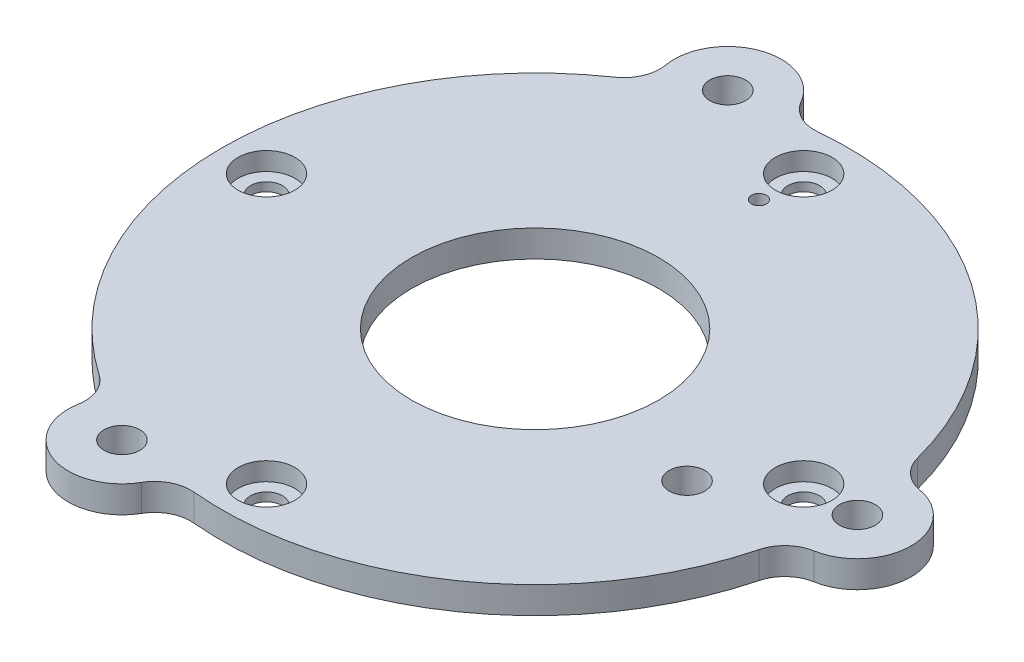
SolidWorks part; units mm, degrees
material "1060 Alloy"
ref_plane "Front Plane" through (0, 0, 0) normal (0, 0, 1) x (1, 0, 0)
ref_plane "Top Plane" through (0, 0, 0) normal (0, 1, 0) x (1, 0, 0)
ref_plane "Right Plane" through (0, 0, 0) normal (1, 0, 0) x (0, 0, -1)
sketch "Sketch1" plane through (0, 0, 0) normal (0, 1, 0) x (1, 0, 0)
  circle A0 centre (0, 0) radius 17.5
  dimension "D1" = 35
extrude "Boss-Extrude1" add sketch "Sketch1" along normal blind 1.5
sketch "Sketch6" plane through (0, 1.5, 0) normal (0, 1, 0) x (1, 0, 0)
  line L0 (0, 0) -> (19.3341, -5.1806) construction
  line L1 (0, 0) -> (17.9741, 0) construction
  circle A0 centre (0, 12.5) radius 0.42
  circle A1 centre (11.5911, -3.1058) radius 1
  dimension "D1" = 12.5
  dimension "D3" = 0.84
  dimension "D4" = 2
  dimension "D2" = 0
  dimension "D5" = 12
  dimension "D6" = 15
extrude "Cut-Extrude1" cut sketch "Sketch6" against normal through all both and the other way through all
hole_wizard "CBORE for #0 Socket Head Cap Screw1" positions "Sketch7" profile "Sketch8" counterbore size "#0" standard "ANSI Inch" end condition through all
sketch "Sketch7" plane through (0, 1.5, 0) normal (0, 1, 0) x (1, 0, 0)
  point P0 (0, 15)
  point P2 (-15, 0)
  point P4 (0, -15)
  point P6 (15, 0)
  dimension "D1" = 15
  dimension "D2" = 15
  dimension "D3" = 15
  dimension "D4" = 15
sketch "Sketch8" plane through (0, 1.5, -15) normal (1, 0, 0) x (0, 0, 1)
  line L0 (0, 0) -> (0, 1.5)
  line L1 (0, 1.5) -> (0.889, 1.5)
  line L3 (0.889, 1.5) -> (0.889, 1.016)
  line L4 (0.889, 1.016) -> (1.5875, 1.016)
  line L5 (1.5875, 1.016) -> (1.5875, 0)
  line L7 (1.5875, 0) -> (0, 0)
  line L11 (0, -6.35) -> (0, 107.95) construction
  dimension "Thru Hole Dia." = 1.778
  dimension "Thru Hole Depth" = 1.5
  dimension "C'Bore Dia." = 3.175
  dimension "C'Bore Depth" = 1.016
sketch "Sketch9" plane through (0, 0, 0) normal (0, -1, 0) x (1, 0, 0)
  line L0 (-6.1564, 16.9145) -> (0, 0) construction
  line L1 (0, 0) -> (-6.1564, -16.9145) construction
  line L2 (-6.1564, -16.9145) -> (0, 0) construction
  line L3 (0, 0) -> (18, 0) construction
  line L4 (-3.2616, 17.702) -> (2.8948, 0.7876)
  line L5 (-8.8801, 15.6571) -> (-2.7238, -1.2574)
  line L6 (17.75, 2.9896) -> (-0.25, 2.9896)
  line L7 (17.75, -2.9896) -> (-0.25, -2.9896)
  line L8 (-8.8801, -15.6571) -> (-2.7238, 1.2574)
  line L9 (-3.2616, -17.702) -> (2.8948, -0.7876)
  circle A0 centre (0, 0) radius 18
  circle A1 centre (-6.1564, 16.9145) radius 1
  circle A2 centre (-6.1564, -16.9145) radius 1
  circle A3 centre (18, 0) radius 1
  circle A4 centre (18, 0) radius 3
  circle A5 centre (-6.1564, -16.9145) radius 3
  circle A6 centre (-6.1564, 16.9145) radius 3
  circle A7 centre (0, 0) radius 3
  circle M10 centre (0, 0) radius 17.5
  dimension "D1" = 2
  dimension "D2" = 2
  dimension "D3" = 2
  dimension "D4" = 36
  dimension "D7" = 6
  dimension "D8" = 6
  dimension "D9" = 6
  dimension "D10" = 6
  dimension "D5" = 140
  dimension "D6" = 110
extrude "Boss-Extrude2" add sketch "Sketch9" against normal up to surface (1.5 mm away) contours A0 A4 A3 | A4 L6 M10 | A4 L7 M10 | A0 A5 A2 | A0 A5 A2 M10 | A5 L9 M10 | A5 L8 M10 | A0 A6 A1 | A6 A0 A1 M10 | A6 L4 M10 | A6 L5 M10 | A5 A0 A2 M10 | A0 A5 A2 M10 | A4 A0 A3 M10 | A0 A4 A3 M10 | A0 A6 A1 M10 | A6 A0 A1 M10
fillet "Fillet1" radius 2 6 edges at (17.2428, 0.75, 2.9896) (-3.0881, 0.75, 17.2254) (-8.7066, 0.75, 15.1804) (-8.7066, 0.75, -15.1804) (-3.0881, 0.75, -17.2254) (17.2428, 0.75, -2.9896)
sketch "Sketch10" plane through (0, 1.5, 0) normal (0, 1, 0) x (1, 0, 0)
  circle A0 centre (-6.1564, 16.9145) radius 1
  circle A1 centre (18, 0) radius 1
  circle A2 centre (-6.1564, -16.9145) radius 1
extrude "Cut-Extrude2" cut sketch "Sketch10" against normal blind 10
sketch "Sketch11" plane through (0, 1.5, 0) normal (0, 1, 0) x (1, 0, 0)
  circle A0 centre (0, 0) radius 6.9
  dimension "D1" = 13.8
extrude "Cut-Extrude3" cut sketch "Sketch11" against normal blind 10
